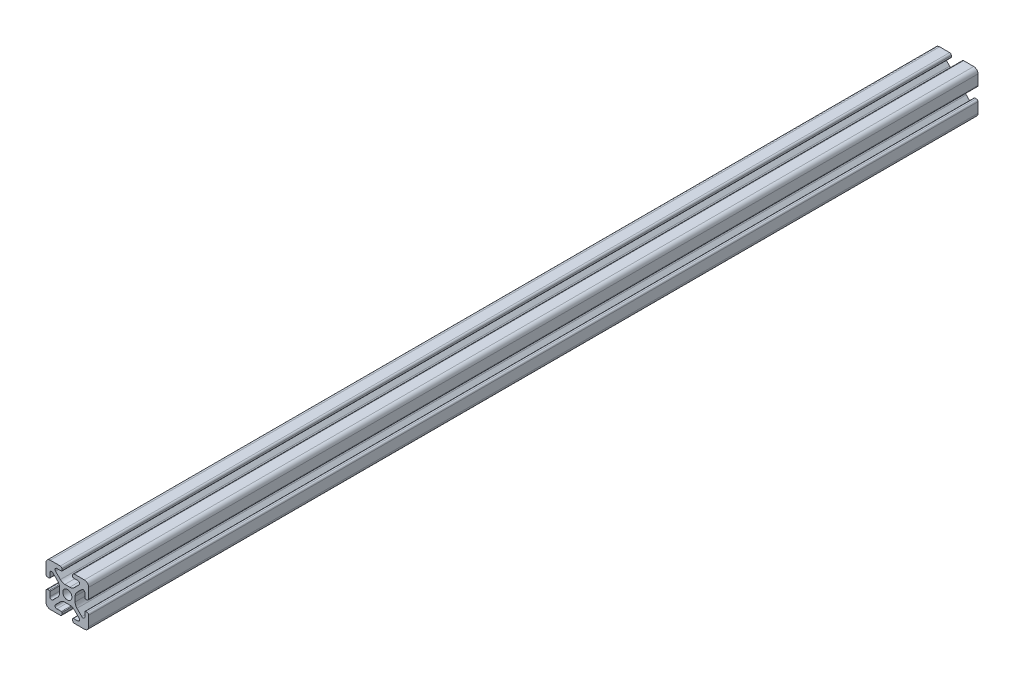
SolidWorks part; units mm, degrees
ref_plane "Front Plane" through (0, 0, 0) normal (0, 0, 1) x (1, 0, 0)
ref_plane "Top Plane" through (0, 0, 0) normal (0, 1, 0) x (1, 0, 0)
ref_plane "Right Plane" through (0, 0, 0) normal (1, 0, 0) x (0, 0, -1)
sketch "Sketch1" plane through (0, 0, 0) normal (0, 0, 1) x (1, 0, 0)
  line L2 (-9.9949, 7.9883) -> (-9.9949, 3.2893)
  line L3 (-7.9883, 9.9949) -> (-3.2893, 9.9949)
  line L4 (-2.5019, 9.2075) -> (-2.5019, 8.4963)
  line L5 (-2.8067, 8.1915) -> (-4.9149, 8.1915)
  line L6 (-5.5076, 6.7606) -> (-3.2528, 4.5058)
  line L7 (-6.7606, 5.5076) -> (-4.5058, 3.2528)
  line L8 (-8.1915, 4.9149) -> (-8.1915, 2.8067)
  line L9 (-8.4963, 2.5019) -> (-9.2075, 2.5019)
  line L11 (-1.1334, 3.6279) -> (1.1334, 3.6279)
  line L12 (-3.6279, 1.1334) -> (-3.6279, -1.1334)
  line L13 (8.4963, 2.5019) -> (9.2075, 2.5019)
  line L14 (8.1915, 4.9149) -> (8.1915, 2.8067)
  line L15 (9.9949, 7.9883) -> (9.9949, 3.2893)
  line L16 (7.9883, 9.9949) -> (3.2893, 9.9949)
  line L17 (2.5019, 9.2075) -> (2.5019, 8.4963)
  line L18 (2.8067, 8.1915) -> (4.9149, 8.1915)
  line L19 (3.6279, 1.1334) -> (3.6279, -1.1334)
  line L20 (5.5076, 6.7606) -> (3.2528, 4.5058)
  line L21 (6.7606, 5.5076) -> (4.5058, 3.2528)
  line L22 (-8.4963, -2.5019) -> (-9.2075, -2.5019)
  line L23 (-8.1915, -4.9149) -> (-8.1915, -2.8067)
  line L24 (-6.7606, -5.5076) -> (-4.5058, -3.2528)
  line L25 (-5.5076, -6.7606) -> (-3.2528, -4.5058)
  line L26 (-2.8067, -8.1915) -> (-4.9149, -8.1915)
  line L27 (-2.5019, -9.2075) -> (-2.5019, -8.4963)
  line L28 (-7.9883, -9.9949) -> (-3.2893, -9.9949)
  line L29 (-9.9949, -7.9883) -> (-9.9949, -3.2893)
  line L30 (9.9949, -7.9883) -> (9.9949, -3.2893)
  line L31 (7.9883, -9.9949) -> (3.2893, -9.9949)
  line L32 (2.5019, -9.2075) -> (2.5019, -8.4963)
  line L33 (2.8067, -8.1915) -> (4.9149, -8.1915)
  line L34 (5.5076, -6.7606) -> (3.2528, -4.5058)
  line L35 (6.7606, -5.5076) -> (4.5058, -3.2528)
  line L36 (8.1915, -4.9149) -> (8.1915, -2.8067)
  line L37 (8.4963, -2.5019) -> (9.2075, -2.5019)
  line L38 (-1.1334, -3.6279) -> (1.1334, -3.6279)
  circle A0 centre (0, 0) radius 2.1463
  arc A1 (-9.9949, 7.9883) -> (-7.9883, 9.9949) centre (-7.9883, 7.9883) cw
  arc A2 (-6.7606, 5.5076) -> (-8.1915, 4.9149) centre (-7.3533, 4.9149) ccw
  arc A3 (-4.9149, 8.1915) -> (-5.5076, 6.7606) centre (-4.9149, 7.3533) ccw
  arc A4 (-3.2893, 9.9949) -> (-2.5019, 9.2075) centre (-3.2893, 9.2075) cw
  arc A5 (-9.9949, 3.2893) -> (-9.2075, 2.5019) centre (-9.2075, 3.2893) ccw
  arc A6 (-8.1915, 2.8067) -> (-8.4963, 2.5019) centre (-8.4963, 2.8067) cw
  arc A7 (-2.5019, 8.4963) -> (-2.8067, 8.1915) centre (-2.8067, 8.4963) cw
  arc A8 (-1.1334, 3.6279) -> (-3.2528, 4.5058) centre (-1.1334, 6.6251) cw
  arc A9 (-3.6279, 1.1334) -> (-4.5058, 3.2528) centre (-6.6251, 1.1334) ccw
  arc A10 (8.1915, 2.8067) -> (8.4963, 2.5019) centre (8.4963, 2.8067) ccw
  arc A11 (9.9949, 3.2893) -> (9.2075, 2.5019) centre (9.2075, 3.2893) cw
  arc A12 (9.9949, 7.9883) -> (7.9883, 9.9949) centre (7.9883, 7.9883) ccw
  arc A13 (3.2893, 9.9949) -> (2.5019, 9.2075) centre (3.2893, 9.2075) ccw
  arc A14 (2.5019, 8.4963) -> (2.8067, 8.1915) centre (2.8067, 8.4963) ccw
  arc A15 (1.1334, 3.6279) -> (3.2528, 4.5058) centre (1.1334, 6.6251) ccw
  arc A16 (3.6279, 1.1334) -> (4.5058, 3.2528) centre (6.6251, 1.1334) cw
  arc A17 (6.7606, 5.5076) -> (8.1915, 4.9149) centre (7.3533, 4.9149) cw
  arc A18 (4.9149, 8.1915) -> (5.5076, 6.7606) centre (4.9149, 7.3533) cw
  arc A19 (-3.6279, -1.1334) -> (-4.5058, -3.2528) centre (-6.6251, -1.1334) cw
  arc A20 (-1.1334, -3.6279) -> (-3.2528, -4.5058) centre (-1.1334, -6.6251) ccw
  arc A21 (-2.5019, -8.4963) -> (-2.8067, -8.1915) centre (-2.8067, -8.4963) ccw
  arc A22 (-8.1915, -2.8067) -> (-8.4963, -2.5019) centre (-8.4963, -2.8067) ccw
  arc A23 (-9.9949, -3.2893) -> (-9.2075, -2.5019) centre (-9.2075, -3.2893) cw
  arc A24 (-3.2893, -9.9949) -> (-2.5019, -9.2075) centre (-3.2893, -9.2075) ccw
  arc A25 (-4.9149, -8.1915) -> (-5.5076, -6.7606) centre (-4.9149, -7.3533) cw
  arc A26 (-6.7606, -5.5076) -> (-8.1915, -4.9149) centre (-7.3533, -4.9149) cw
  arc A27 (-9.9949, -7.9883) -> (-7.9883, -9.9949) centre (-7.9883, -7.9883) ccw
  arc A28 (9.9949, -7.9883) -> (7.9883, -9.9949) centre (7.9883, -7.9883) cw
  arc A29 (6.7606, -5.5076) -> (8.1915, -4.9149) centre (7.3533, -4.9149) ccw
  arc A30 (4.9149, -8.1915) -> (5.5076, -6.7606) centre (4.9149, -7.3533) ccw
  arc A31 (3.2893, -9.9949) -> (2.5019, -9.2075) centre (3.2893, -9.2075) cw
  arc A32 (9.9949, -3.2893) -> (9.2075, -2.5019) centre (9.2075, -3.2893) ccw
  arc A33 (8.1915, -2.8067) -> (8.4963, -2.5019) centre (8.4963, -2.8067) cw
  arc A34 (2.5019, -8.4963) -> (2.8067, -8.1915) centre (2.8067, -8.4963) cw
  arc A35 (1.1334, -3.6279) -> (3.2528, -4.5058) centre (1.1334, -6.6251) cw
  arc A36 (3.6279, -1.1334) -> (4.5058, -3.2528) centre (6.6251, -1.1334) ccw
extrude "Boss-Extrude1" add sketch "Sketch1" along normal mid plane 416.3822
